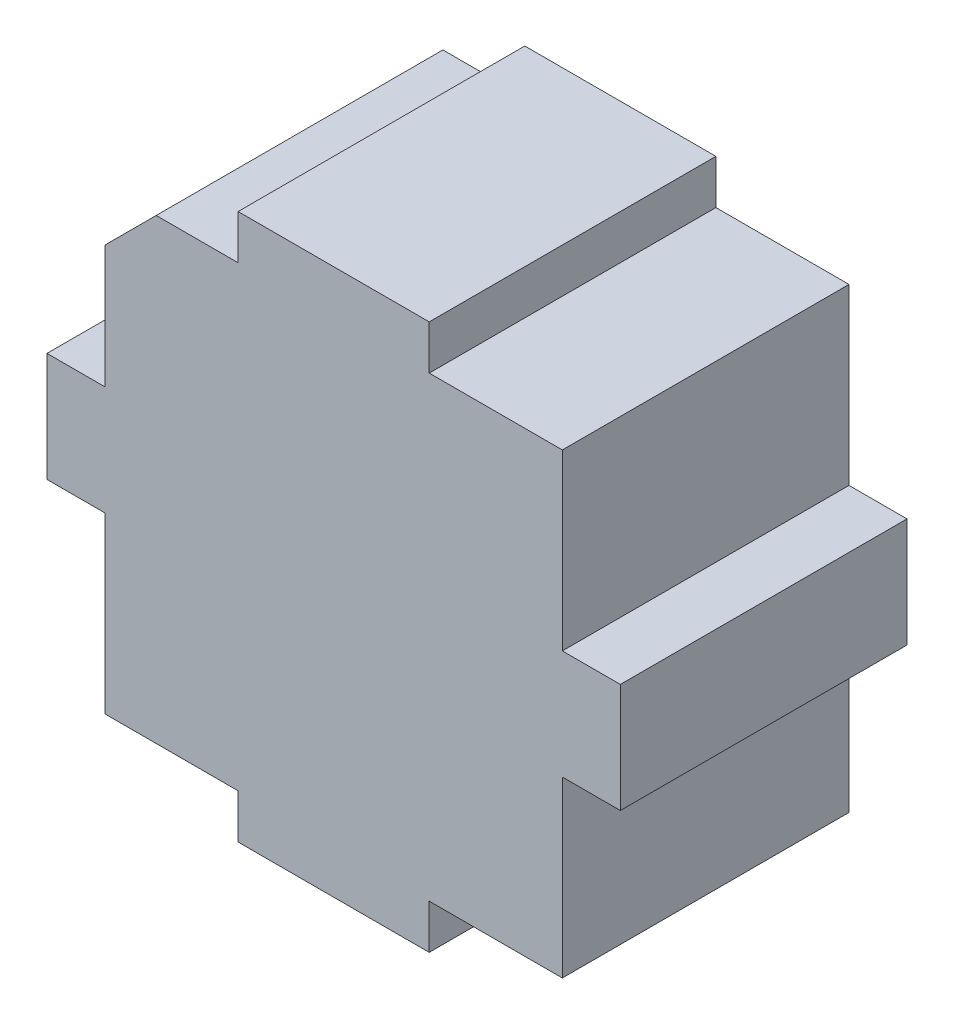
SolidWorks part; units mm, degrees
ref_plane "前视基准面" through (0, 0, 0) normal (0, 0, 1) x (1, 0, 0)
ref_plane "上视基准面" through (0, 0, 0) normal (0, 1, 0) x (1, 0, 0)
ref_plane "右视基准面" through (0, 0, 0) normal (1, 0, 0) x (0, 0, -1)
sketch "草图1" plane through (0, 0, 0) normal (0, 0, 1) x (1, 0, 0)
  line L0 (0.7, 2) -> (0.7, 1.675)
  line L1 (0.7, 1.675) -> (1.675, 1.675)
  line L2 (1.675, 1.675) -> (1.675, 0.4)
  line L3 (1.675, 0.4) -> (2.1, 0.4)
  line L4 (2.1, 0.4) -> (2.1, -0.4)
  line L5 (2.1, -0.4) -> (1.675, -0.4)
  line L6 (1.675, -0.4) -> (1.675, -1.675)
  line L7 (1.675, -1.675) -> (0.7, -1.675)
  line L8 (0.7, -1.675) -> (0.7, -2)
  line L9 (0.7, -2) -> (-0.7, -2)
  line L10 (-0.7, -2) -> (-0.7, -1.675)
  line L11 (-0.7, -1.675) -> (-1.675, -1.675)
  line L12 (-1.675, -1.675) -> (-1.675, -0.4)
  line L13 (-1.675, -0.4) -> (-2.1, -0.4)
  line L14 (-2.1, -0.4) -> (-2.1, 0.4)
  line L15 (-2.1, 0.4) -> (-1.675, 0.4)
  line L16 (-1.675, 0.4) -> (-1.675, 1.3)
  line L17 (-1.675, 1.3) -> (-1.3, 1.675)
  line L18 (-1.3, 1.675) -> (-0.7, 1.675)
  line L19 (-0.7, 1.675) -> (-0.7, 2)
  line L20 (-0.7, 2) -> (0.7, 2)
extrude "Component_Outline" add sketch "草图1" along normal blind 2.1 separate body
sketch3d "3D草图1"
  line L0 (0, 0, 0) -> (1, 0, 0)
  line L1 (0, 0, 0) -> (0, 1, 0)
  line L2 (0, 0, 0) -> (0, 0, 1)
  point P0 (0, 0, 0)
